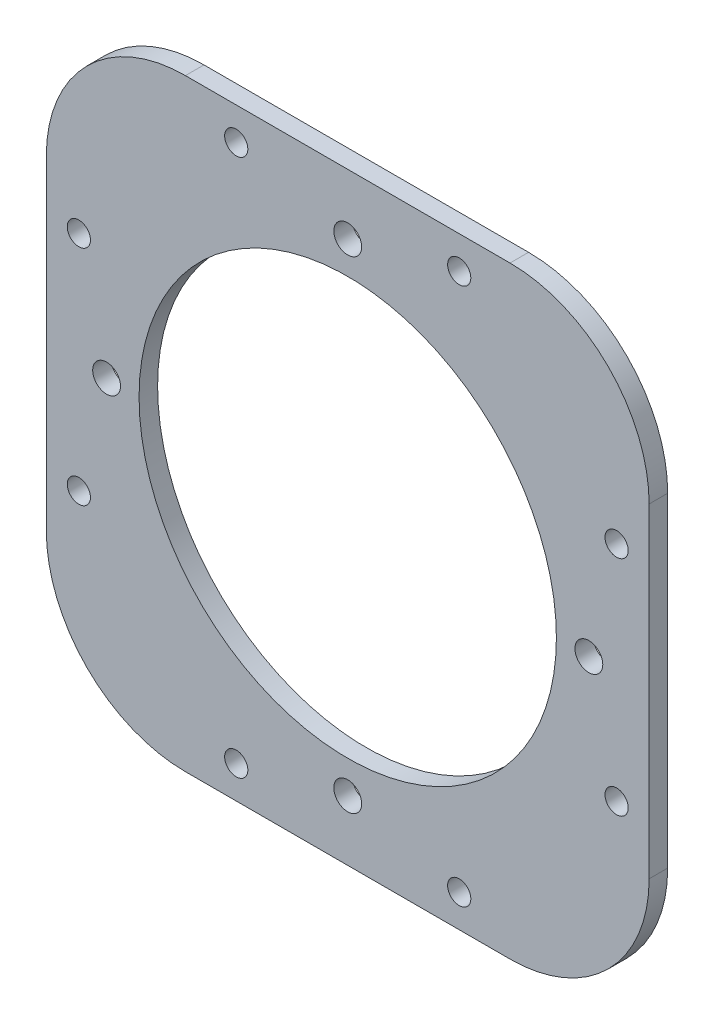
SolidWorks part; units mm, degrees
material "Thornel Mat VMA"
ref_plane "Alzado" through (0, 0, 0) normal (0, 0, 1) x (1, 0, 0)
ref_plane "Planta" through (0, 0, 0) normal (0, 1, 0) x (1, 0, 0)
ref_plane "Vista lateral" through (0, 0, 0) normal (1, 0, 0) x (0, 0, -1)
sketch "Croquis1" plane through (0, 0, 0) normal (0, 0, 1) x (1, 0, 0)
  line L0 (0, 0) -> (0, 32.5) construction
  line L1 (32.5, -32.5) -> (-32.5, -32.5)
  line L2 (32.5, -32.5) -> (32.5, 32.5)
  line L3 (32.5, 32.5) -> (-32.5, 32.5)
  line L4 (-32.5, -32.5) -> (-32.5, 32.5)
  line L5 (32.5, -32.5) -> (-32.5, 32.5) construction
  line L6 (32.5, 32.5) -> (-32.5, -32.5) construction
  line L7 (21.9203, 21.9203) -> (31.8198, 12.0208) construction
  line L8 (31.8198, 12.0208) -> (28.9914, 9.1924) construction
  line L9 (28.9914, 9.1924) -> (19.0919, 19.0919) construction
  line L10 (9.1924, 28.9914) -> (12.0208, 31.8198) construction
  line L11 (12.0208, 31.8198) -> (21.9203, 21.9203) construction
  line L12 (19.0919, 19.0919) -> (9.1924, 28.9914) construction
  circle A0 centre (0, 0) radius 22.5
  circle A1 centre (-27.5503, 27.5503) radius 3 construction
  circle A2 centre (27.5503, 27.5503) radius 3 construction
  circle A3 centre (27.5503, -27.5503) radius 3 construction
  circle A4 centre (-27.5503, -27.5503) radius 3 construction
  circle A5 centre (0, 26) radius 1.5
  circle A6 centre (26, 0) radius 1.5
  circle A7 centre (0, -26) radius 1.5
  circle A8 centre (-26, 0) radius 1.5
  circle A9 centre (0, 0) radius 26 construction
  circle A10 centre (12.0208, 28.9914) radius 1.25
  circle A11 centre (28.9914, 12.0208) radius 1.25
  circle A12 centre (12.0208, -28.9914) radius 1.25
  circle A13 centre (28.9914, -12.0208) radius 1.25
  circle A14 centre (-28.9914, -12.0208) radius 1.25
  circle A15 centre (-12.0208, -28.9914) radius 1.25
  circle A16 centre (-12.0208, 28.9914) radius 1.25
  circle A17 centre (-28.9914, 12.0208) radius 1.25
  point P0 (0, 0)
  point P19 (0, 0)
  point P28 (0, 0)
  point P53 (0, 0)
  dimension "D1" = 45
  dimension "D3" = 6
  dimension "D7" = 52
  dimension "D9" = 3
  dimension "D10" = 27
  dimension "D14" = 2.5
  dimension "D2" = 7
  dimension "D4" = 65
  dimension "D5" = 65
  dimension "D11" = 14
  dimension "D12" = 4
  dimension "D13" = 28
  dimension "D15" = 2
  dimension "D16" = 2
  dimension "D6" = 4
  dimension "D8" = 4
  dimension "D17" = 4
extrude "Saliente-Extruir1" add sketch "Croquis1" along normal blind 2
fillet "Redondeo1" radius 15 4 edges at (32.5, -32.5, 1) (-32.5, -32.5, 1) (32.5, 32.5, 1) (-32.5, 32.5, 1)
